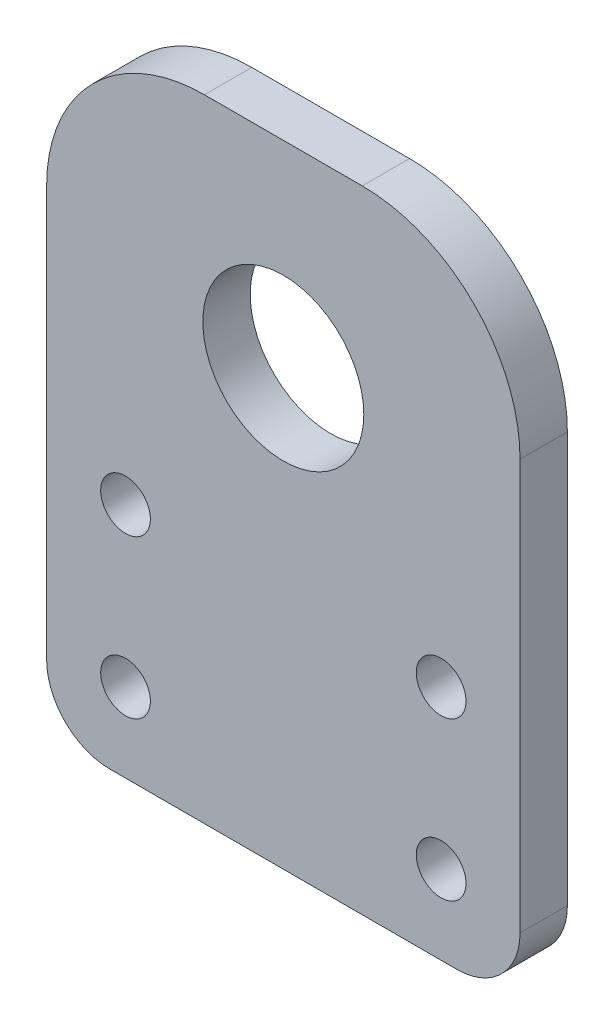
SolidWorks part; units mm, degrees
ref_plane "前视基准面" through (0, 0, 0) normal (0, 0, 1) x (1, 0, 0)
ref_plane "上视基准面" through (0, 0, 0) normal (0, 1, 0) x (1, 0, 0)
ref_plane "右视基准面" through (0, 0, 0) normal (1, 0, 0) x (0, 0, -1)
other "Configuration Table"
sketch "草图1" plane through (0, 0, 0) normal (0, 0, 1) x (1, 0, 0)
  line L1 (0, 0) -> (30, 0)
  line L2 (0, 0) -> (0, -40)
  line L3 (0, -40) -> (30, -40)
  line L4 (30, 0) -> (30, -40)
  dimension "D1" = 30
  dimension "D2" = 40
extrude "凸台-拉伸1" add sketch "草图1" along normal blind 3
sketch "草图2" plane through (0, 0, 3) normal (0, 0, 1) x (1, 0, 0)
  line L0 (15, 0) -> (15, -40) construction
  line L1 (30, 0) -> (0, 0) construction
  line L2 (0, -40) -> (30, -40) construction
  line L3 (0, -30) -> (15, -30) construction
  line L4 (0, 0) -> (0, -40) construction
  line L5 (0, -20) -> (30, -20) construction
  line L6 (30, -40) -> (30, 0) construction
  circle A0 centre (15, -12.5) radius 5.1
  circle A1 centre (5, -25) radius 1.575
  circle A2 centre (5, -35) radius 1.575
  circle A3 centre (25, -35) radius 1.575
  circle A4 centre (25, -25) radius 1.575
  dimension "D1" = 10.2
  dimension "D3" = 3.15
  dimension "D2" = 7.5
  dimension "D4" = 10
  dimension "D5" = 5
  dimension "D6" = 10
extrude "切除-拉伸1" cut sketch "草图2" against normal through all
fillet "圆角1" radius 10 2 edges at (30, 0, 1.5) (0, 0, 1.5)
fillet "圆角2" radius 4 2 edges at (30, -40, 1.5) (0, -40, 1.5)
